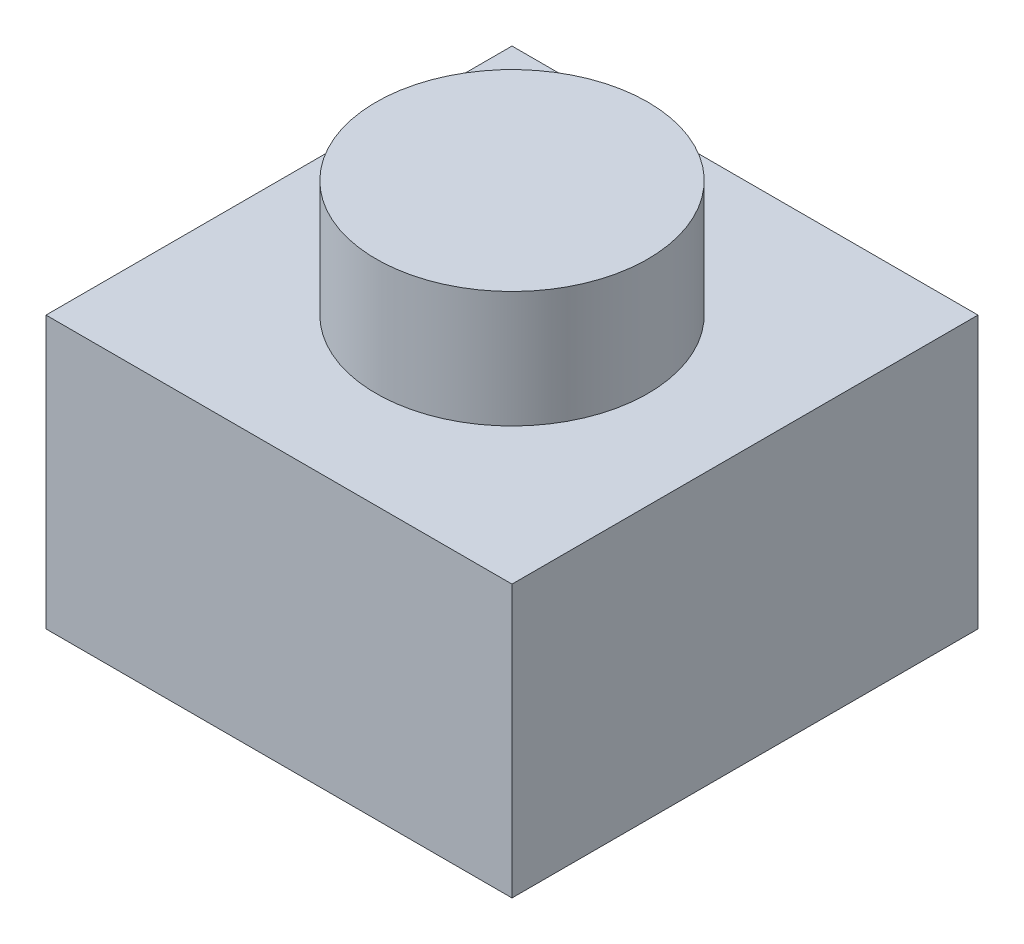
SolidWorks part; units mm, degrees
ref_plane "Front Plane" through (0, 0, 0) normal (0, 0, 1) x (1, 0, 0)
ref_plane "Top Plane" through (0, 0, 0) normal (0, 1, 0) x (1, 0, 0)
ref_plane "Right Plane" through (0, 0, 0) normal (1, 0, 0) x (0, 0, -1)
sketch "Sketch1" plane through (0, 0, 0) normal (0, 1, 0) x (1, 0, 0)
  line L1 (0, 0) -> (6.096, 0)
  line L2 (0, 0) -> (0, 6.096)
  line L3 (0, 6.096) -> (6.096, 6.096)
  line L4 (6.096, 0) -> (6.096, 6.096)
  dimension "D1" = 6.096
extrude "Boss-Extrude1" add sketch "Sketch1" along normal blind 3.556
sketch "Sketch2" plane through (0, 3.556, 0) normal (0, 1, 0) x (1, 0, 0)
  line L0 (0, 6.096) -> (6.096, 0) construction
  line L1 (0, 0) -> (6.096, 0) construction
  circle A0 centre (3.048, 3.048) radius 1.778
  point P7 (2.5869, 2.5827)
  point P8 (3.048, 3.048)
  dimension "D1" = 3.556
extrude "Boss-Extrude2" add sketch "Sketch2" along normal blind 1.524
